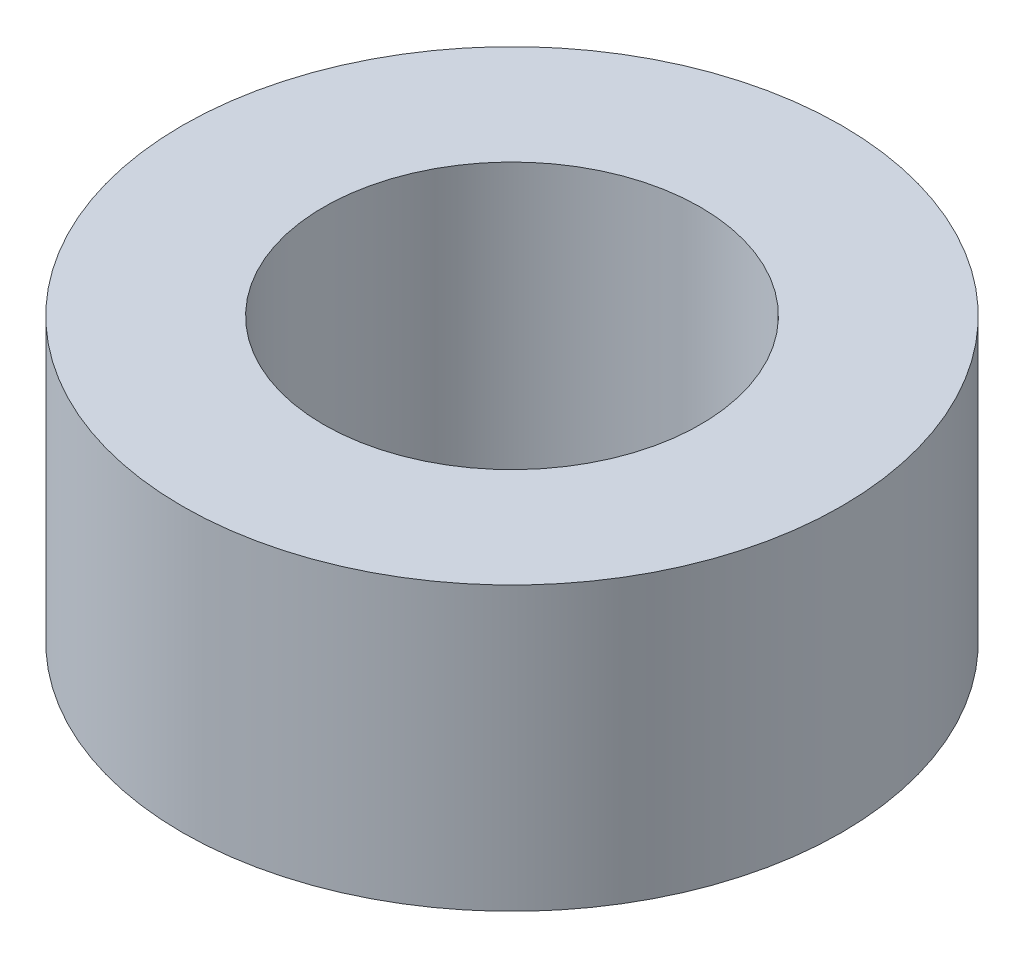
SolidWorks part; units mm, degrees
ref_plane "Спереди" through (0, 0, 0) normal (0, 0, 1) x (1, 0, 0)
ref_plane "Сверху" through (0, 0, 0) normal (0, 1, 0) x (1, 0, 0)
ref_plane "Справа" through (0, 0, 0) normal (1, 0, 0) x (0, 0, -1)
sketch "Эскиз1" plane through (0, 0, 0) normal (0, 1, 0) x (1, 0, 0)
  circle A0 centre (0, 0) radius 2
  circle A1 centre (0, 0) radius 3.5
  dimension "D1" = 4
  dimension "D2" = 7
extrude "Бобышка-Вытянуть1" add sketch "Эскиз1" along normal blind 3
